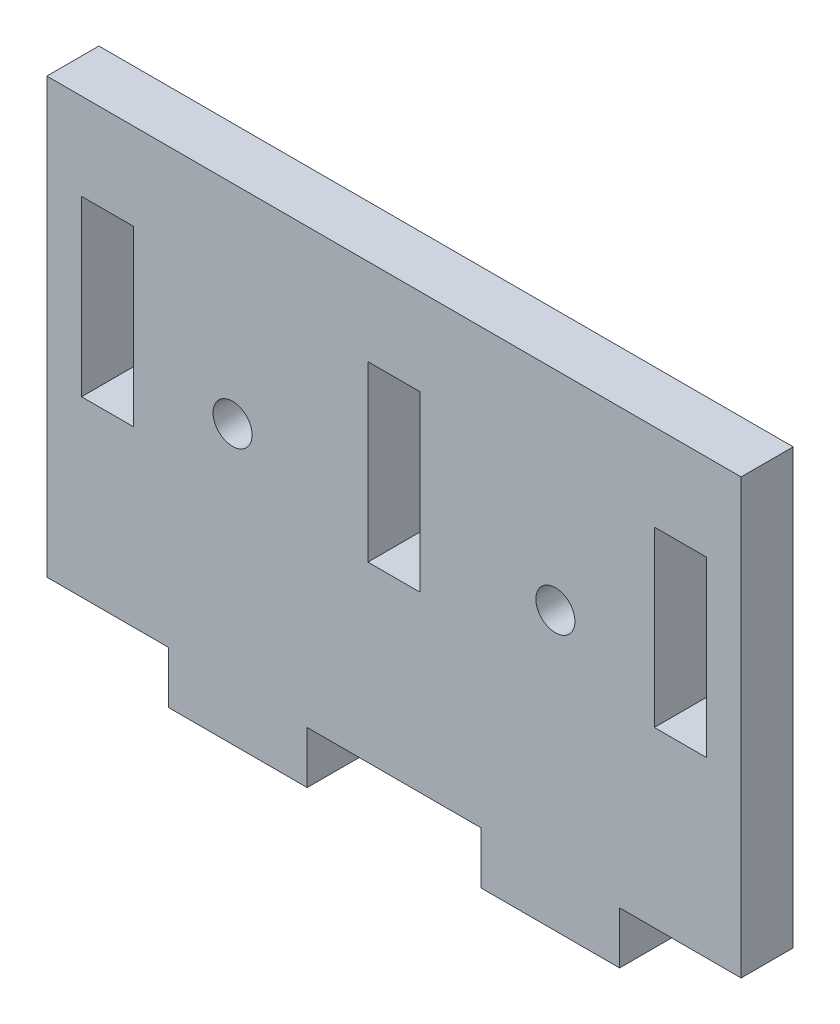
SolidWorks part; units mm, degrees
material "ABS PC"
ref_plane "前视基准面" through (0, 0, 0) normal (0, 0, 1) x (1, 0, 0)
ref_plane "上视基准面" through (0, 0, 0) normal (0, 1, 0) x (1, 0, 0)
ref_plane "右视基准面" through (0, 0, 0) normal (1, 0, 0) x (0, 0, -1)
sketch "草图1" plane through (0, 0, 0) normal (0, 0, 1) x (1, 0, 0)
  line L15 (40, 0) -> (40, 25)
  line L16 (40, 25) -> (0, 25)
  line L17 (0, 25) -> (0, 0)
  line L20 (0, 0) -> (2, 0)
  line L26 (2, 10) -> (5, 10)
  line L33 (2, 0) -> (5, 0)
  line L34 (35, 20) -> (35, 10)
  line L35 (5, 0) -> (7, 0)
  line L36 (7, 0) -> (7, -3)
  line L37 (7, -3) -> (15, -3)
  line L38 (15, -3) -> (15, 0)
  line L39 (15, 0) -> (25, 0)
  line L40 (38, 20) -> (35, 20)
  line L41 (2, 10) -> (2, 20)
  line L42 (2, 20) -> (5, 20)
  line L43 (5, 20) -> (5, 10)
  line L44 (38, 10) -> (38, 20)
  line L45 (25, -3) -> (25, 0)
  line L46 (33, -3) -> (25, -3)
  line L47 (33, 0) -> (33, -3)
  line L48 (35, 0) -> (33, 0)
  line L49 (38, 0) -> (35, 0)
  line L50 (38, 10) -> (35, 10)
  line L51 (40, 0) -> (38, 0)
  line L52 (40, 25) -> (40, 0)
  line L53 (21.5, 20) -> (20, 20)
  line L54 (21.5, 20) -> (18.5, 20)
  line L55 (18.5, 20) -> (18.5, 10)
  line L56 (18.5, 10) -> (21.5, 10)
  line L57 (21.5, 20) -> (21.5, 10)
  line L58 (20, 25) -> (10.7, 25)
  circle A0 centre (10.7, 13) radius 1.125
  circle A1 centre (29.3, 13) radius 1.125
  point P20 (5, 15)
  point P21 (2, 15)
  point P29 (38, 15)
  point P30 (35, 15)
  point P36 (20, 10)
  dimension "D14" = 2.25
  dimension "D1" = 40
  dimension "D2" = 25
  dimension "D3" = 2
  dimension "D4" = 3
  dimension "D5" = 2
  dimension "D6" = 8
  dimension "D7" = 3
  dimension "D8" = 5
  dimension "D9" = 1.5
  dimension "D10" = 10
  dimension "D11" = 12
  dimension "D12" = 12
  dimension "D13" = 18.6
  dimension "D15" = 9.3
extrude "凸台-拉伸1" add sketch "草图1" along normal blind 3 contours L51 L15 L16 L17 L20 L33 L35 L36 L37 L38 L39 L45 L46 L47 L48 L49 L42 L43 L26 L41 L44 L50 L34 L40
